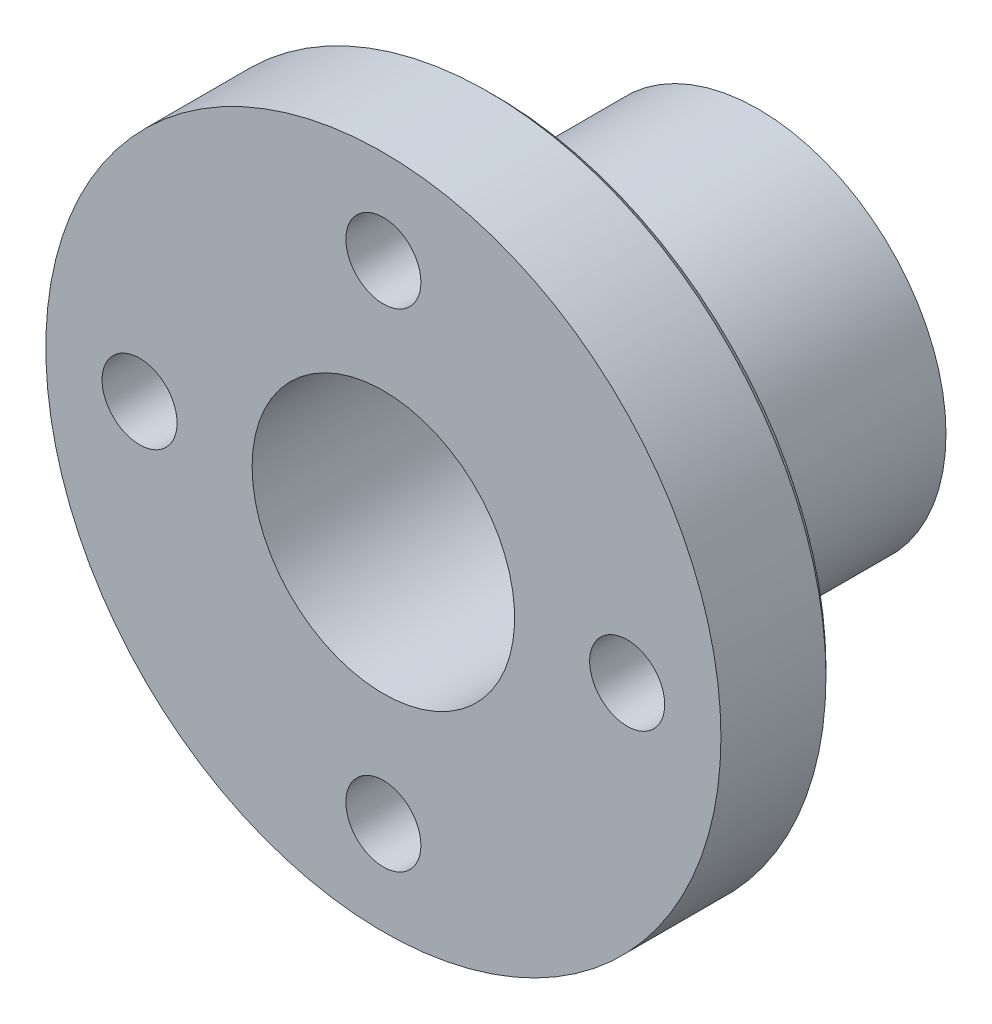
SolidWorks part; units mm, degrees
material "Plain Carbon Steel"
ref_plane "Front Plane" through (0, 0, 0) normal (0, 0, 1) x (1, 0, 0)
ref_plane "Top Plane" through (0, 0, 0) normal (0, 1, 0) x (1, 0, 0)
ref_plane "Right Plane" through (0, 0, 0) normal (1, 0, 0) x (0, 0, -1)
sketch "Sketch1" plane through (0, 0, 0) normal (0, 0, 1) x (1, 0, 0)
  circle A0 centre (0, 0) radius 45
  circle A1 centre (0, 0) radius 32.5 construction
  circle A2 centre (0, 32.5) radius 5
  circle A3 centre (32.5, 0) radius 5
  circle A4 centre (0, -32.5) radius 5
  circle A5 centre (-32.5, 0) radius 5
  point P15 (0, 0)
  dimension "D1" = 65
  dimension "D2" = 90
  dimension "D3" = 10
  dimension "D4" = 4
extrude "Boss-Extrude1" add sketch "Sketch1" against normal blind 15
sketch "Sketch3" plane through (0, 0, -15) normal (0, 0, -1) x (-1, 0, 0)
  circle A0 centre (0, 0) radius 25
  dimension "D1" = 50
extrude "Boss-Extrude2" add sketch "Sketch3" along normal blind 35
fillet "Fillet1" radius 1 1 edges at (25, 0, -15)
chamfer "Chamfer1" distance 1 angle 45 1 edges at (45, 0, -15)
sketch "Sketch4" plane through (0, 0, -50) normal (0, 0, -1) x (-1, 0, 0)
  circle A0 centre (0, 0) radius 17.5
  dimension "D1" = 35
extrude "Cut-Extrude1" cut sketch "Sketch4" against normal blind 59
